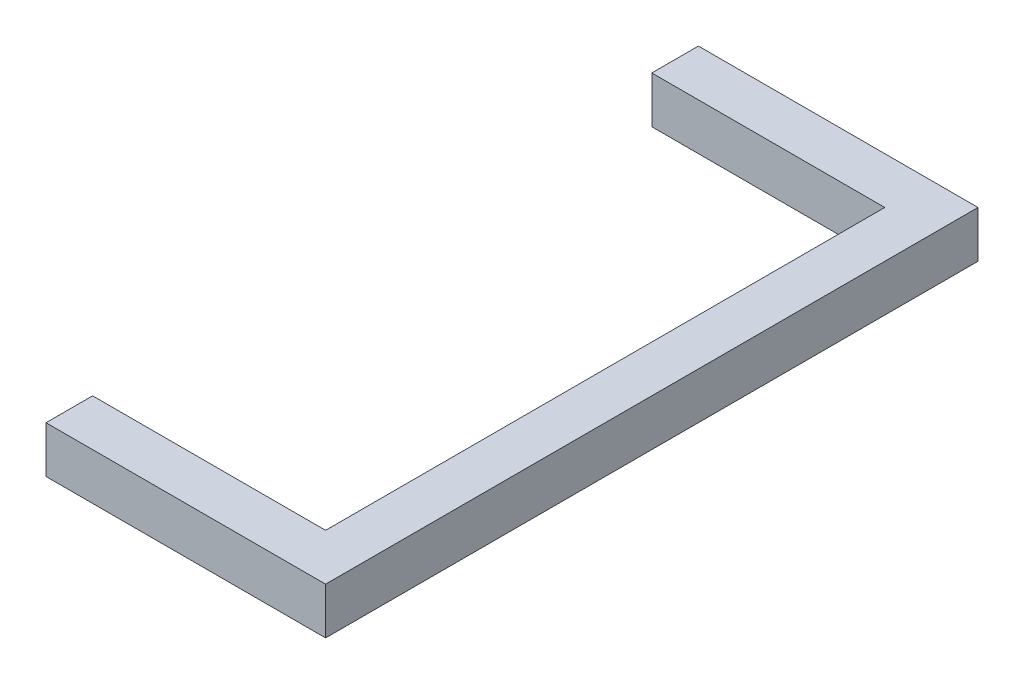
SolidWorks part; units mm, degrees
ref_plane "Front Plane" through (0, 0, 0) normal (0, 0, 1) x (1, 0, 0)
ref_plane "Top Plane" through (0, 0, 0) normal (0, 1, 0) x (1, 0, 0)
ref_plane "Right Plane" through (0, 0, 0) normal (1, 0, 0) x (0, 0, -1)
sketch "Sketch1" plane through (0, 0, 0) normal (0, 1, 0) x (1, 0, 0)
  line L0 (3.175, -22.225) -> (3.175, 22.225)
  line L1 (3.175, 22.225) -> (-15.875, 22.225)
  line L2 (-15.875, 22.225) -> (-15.875, 19.05)
  line L3 (-15.875, 19.05) -> (0, 19.05)
  line L4 (0, 19.05) -> (0, -19.05)
  line L5 (3.175, 0) -> (0, 0) construction
  line L6 (-15.875, -19.05) -> (0, -19.05)
  line L7 (-15.875, -22.225) -> (-15.875, -19.05)
  line L8 (3.175, -22.225) -> (-15.875, -22.225)
  point P11 (0, 0)
  point P12 (10.0499, 0.0036)
  dimension "D1" = 3.175
  dimension "D2" = 44.45
  dimension "D3" = 19.05
extrude "Boss-Extrude1" add sketch "Sketch1" along normal mid plane 3.175
